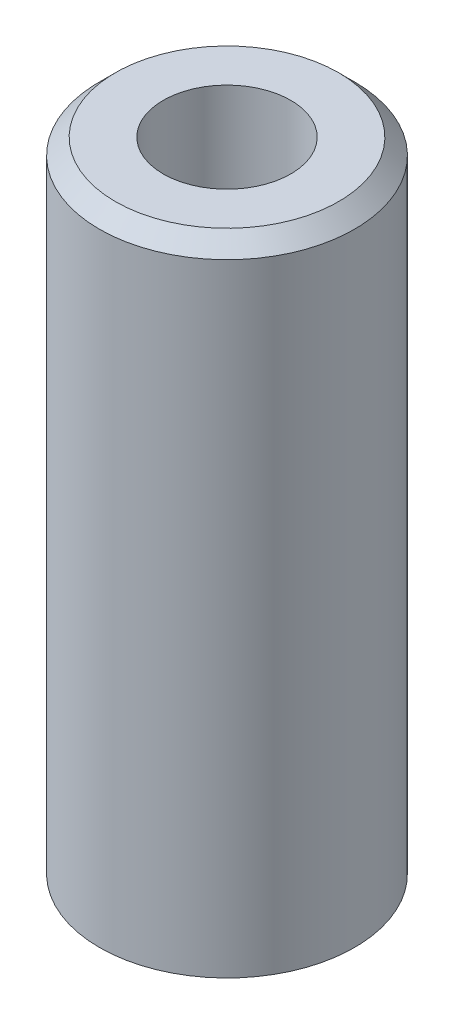
SolidWorks part; units mm, degrees
ref_plane "Front Plane" through (0, 0, 0) normal (0, 0, 1) x (1, 0, 0)
ref_plane "Top Plane" through (0, 0, 0) normal (0, 1, 0) x (1, 0, 0)
ref_plane "Right Plane" through (0, 0, 0) normal (1, 0, 0) x (0, 0, -1)
sketch "Sketch1" plane through (0, 0, 0) normal (0, 1, 0) x (1, 0, 0)
  circle A0 centre (0, 0) radius 2
  circle A1 centre (0, 0) radius 4
  dimension "D1" = 4
  dimension "D2" = 2
extrude "Boss-Extrude1" add sketch "Sketch1" along normal blind 20
chamfer "Chamfer1" distance 0.5 angle 45 1 edges at (0, 20, 4)
